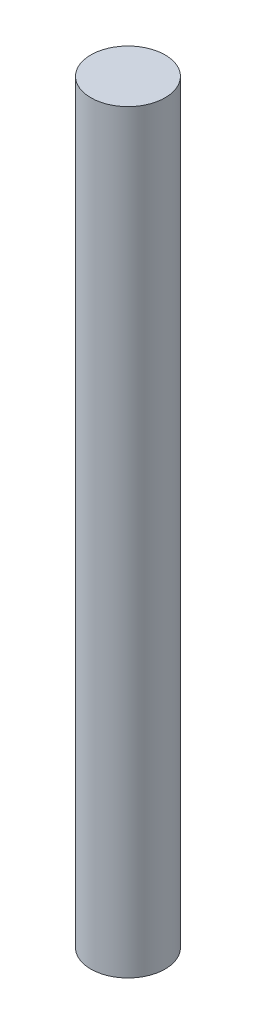
SolidWorks part; units mm, degrees
ref_plane "Front Plane" through (0, 0, 0) normal (0, 0, 1) x (1, 0, 0)
ref_plane "Top Plane" through (0, 0, 0) normal (0, 1, 0) x (1, 0, 0)
ref_plane "Right Plane" through (0, 0, 0) normal (1, 0, 0) x (0, 0, -1)
sketch "Sketch1" plane through (0, 0, 0) normal (0, 1, 0) x (1, 0, 0)
  circle A0 centre (0, 0) radius 2.5
  dimension "D1" = 5
extrude "Boss-Extrude1" add sketch "Sketch1" along normal blind 50.8
